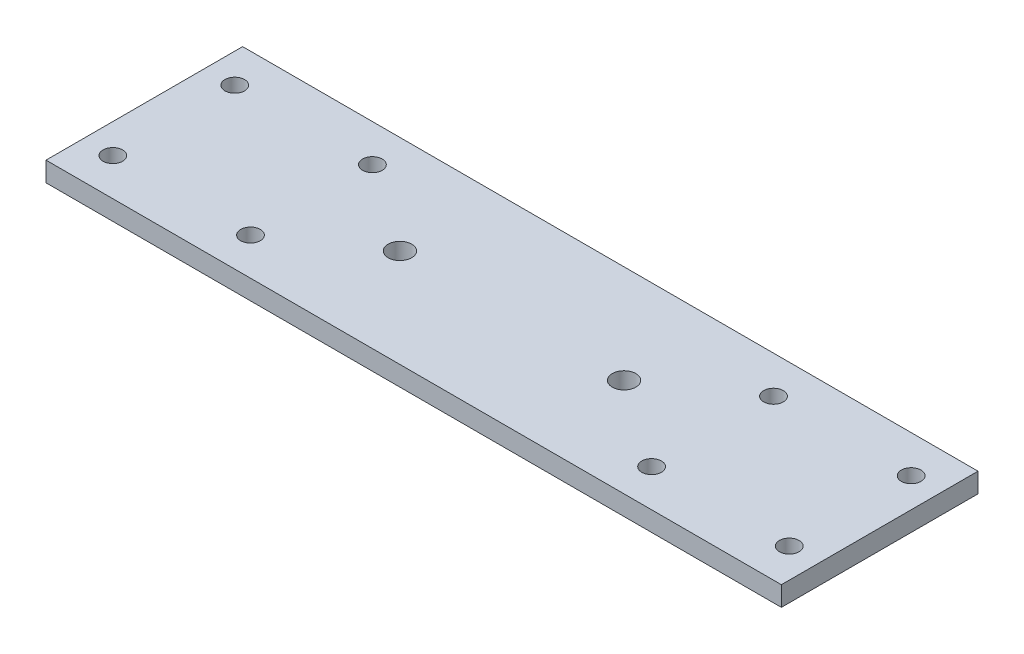
SolidWorks part; units mm, degrees
ref_plane "Front Plane" through (0, 0, 0) normal (0, 0, 1) x (1, 0, 0)
ref_plane "Top Plane" through (0, 0, 0) normal (0, 1, 0) x (1, 0, 0)
ref_plane "Right Plane" through (0, 0, 0) normal (1, 0, 0) x (0, 0, -1)
sketch "Sketch1" plane through (0, 0, 0) normal (0, 1, 0) x (1, 0, 0)
  line L1 (0, 0) -> (187, 0)
  line L2 (0, 0) -> (0, 50)
  line L3 (0, 50) -> (187, 50)
  line L4 (187, 0) -> (187, 50)
  dimension "D1" = 187
  dimension "D2" = 50
extrude "Boss-Extrude1" add sketch "Sketch1" along normal blind 5
sketch "Sketch2" plane through (0, 5, 0) normal (0, 1, 0) x (1, 0, 0)
  line L0 (0, 50) -> (0, 0) construction
  line L1 (187, 0) -> (187, 50) construction
  circle A0 centre (65, 25) radius 3
  circle A1 centre (122, 25) radius 3
  dimension "D1" = 6
  dimension "D3" = 6
  dimension "D2" = 65
  dimension "D4" = 65
extrude "Cut-Extrude1" cut sketch "Sketch2" against normal blind 5
sketch "Sketch3" plane through (0, 5, 0) normal (0, 1, 0) x (1, 0, 0)
  circle A0 centre (144.5, 40.5) radius 2.5
  circle A1 centre (144.5, 9.5) radius 2.5
  circle A2 centre (179.5, 9.5) radius 2.5
  circle A3 centre (179.5, 40.5) radius 2.5
extrude "Cut-Extrude2" cut sketch "Sketch3" against normal blind 5
sketch "Sketch4" plane through (0, 5, 0) normal (0, 1, 0) x (1, 0, 0)
  circle A0 centre (42.5, 9.5) radius 2.5
  circle A1 centre (7.5, 9.5) radius 2.5
  circle A2 centre (7.5, 40.5) radius 2.5
  circle A3 centre (42.5, 40.5) radius 2.5
extrude "Cut-Extrude3" cut sketch "Sketch4" against normal blind 25 contours A2
sketch "Sketch5" plane through (0, 5, 0) normal (0, 1, 0) x (1, 0, 0)
  circle A0 centre (42.5, 9.5) radius 2.5
  circle A1 centre (7.5, 9.5) radius 2.5
  circle A2 centre (42.5, 40.5) radius 2.5
extrude "Cut-Extrude4" cut sketch "Sketch5" against normal blind 25
